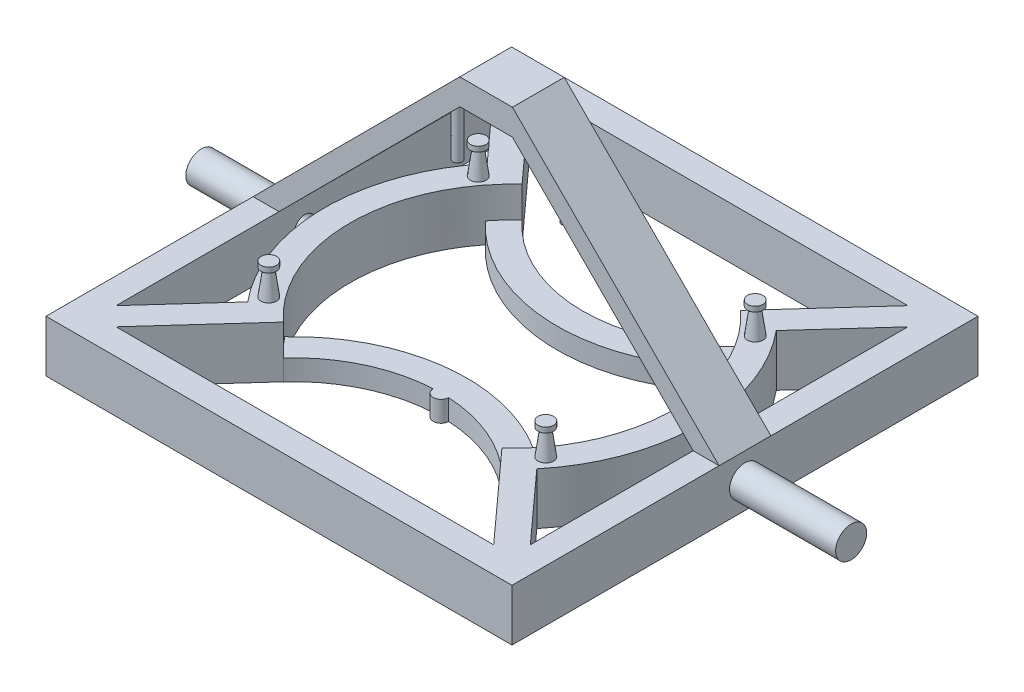
SolidWorks part; units mm, degrees
material "ABS PC"
ref_plane "Front Plane" through (0, 0, 0) normal (0, 0, 1) x (1, 0, 0)
ref_plane "Top Plane" through (0, 0, 0) normal (0, 1, 0) x (1, 0, 0)
ref_plane "Right Plane" through (0, 0, 0) normal (1, 0, 0) x (0, 0, -1)
sketch "Sketch1" plane through (0, 0, 0) normal (0, 1, 0) x (1, 0, 0)
  line L1 (-40, -40) -> (40, -40)
  line L2 (-40, -40) -> (-40, 40)
  line L3 (-40, 40) -> (40, 40)
  line L4 (40, -40) -> (40, 40)
  line L5 (-40, -40) -> (40, 40) construction
  line L6 (-40, 40) -> (40, -40) construction
  line L7 (-45, -45) -> (45, -45)
  line L8 (-45, -45) -> (-45, 45)
  line L9 (-45, 45) -> (45, 45)
  line L10 (45, -45) -> (45, 45)
  line L11 (-45, -45) -> (45, 45) construction
  line L12 (-45, 45) -> (45, -45) construction
  point P0 (0, 0)
  point P6 (0, 0)
  dimension "D1" = 80
  dimension "D2" = 5
extrude "Boss-Extrude1" add sketch "Sketch1" along normal blind 10
sketch "Sketch2" plane through (45, 0, 0) normal (1, 0, 0) x (0, 0, -1)
  line L0 (-45, 0) -> (45, 0) construction
  circle A0 centre (0, 5) radius 3
  dimension "D2" = 6
  dimension "D1" = 5
extrude "Boss-Extrude2" add sketch "Sketch2" along normal blind 20.5
sketch "Sketch3" plane through (0, 0, 0) normal (0, 0, 1) x (1, 0, 0)
  line L0 (-40, 10) -> (-45, 10)
  line L1 (-5.0739, 45) -> (-40, 10)
  line L2 (0, 0) -> (0, 50) construction
  line L3 (-5.0845, 50) -> (5.0845, 50)
  line L4 (5.0845, 50) -> (45, 10)
  line L5 (-5.0739, 45) -> (5.0739, 45)
  line L6 (5.0739, 45) -> (40, 10)
  line L7 (40, 10) -> (45, 10)
  line L8 (-5.0845, 50) -> (-45, 10)
  point P15 (0, 45)
  dimension "D1" = 50
  dimension "D2" = 5
extrude "Boss-Extrude3" add sketch "Sketch3" along normal blind 5 and the other way blind 5
sketch "Sketch4" plane through (-45, 0, 0) normal (-1, 0, 0) x (0, 0, 1)
  line L0 (5, 10) -> (45, 10) construction
  circle A0 centre (0, 5) radius 3
  dimension "D1" = 6
  dimension "D2" = 5
extrude "Boss-Extrude4" add sketch "Sketch4" along normal blind 15
sketch "Sketch5" plane through (0, 0, 0) normal (0, 1, 0) x (1, 0, 0)
  line L0 (-40, -5) -> (-40, -40) construction
  line L1 (-40, -40) -> (40, -40) construction
  line L4 (40, 40) -> (-40, 40) construction
  line L5 (-40, 40) -> (-40, 5) construction
  line L6 (-40, -36.4602) -> (-40, -40)
  line L7 (-40, -40) -> (-36.4602, -40)
  line L10 (-36.4602, 40) -> (-40, 40)
  line L11 (-40, 40) -> (-40, 36.4602)
  line L12 (-36.4602, 40) -> (-21.1018, 23.0494)
  line L13 (-27.9166, 23.1241) -> (-40, 36.4602)
  line L14 (-27.9166, -23.1241) -> (-40, -36.4602)
  line L15 (-36.4602, -40) -> (-21.1018, -23.0494)
  arc A0 (-21.1018, 23.0494) -> (-21.1018, -23.0494) centre (0, 0) ccw
  arc A1 (-27.9166, -23.1241) -> (-27.9166, 23.1241) centre (0, 0) cw
  dimension "D1" = 31.25
  dimension "D2" = 5
  dimension "D3" = 5
  dimension "D4" = 5
extrude "Boss-Extrude5" add sketch "Sketch5" along normal up to surface (10 mm away) up to face at (0, 10, -23.75)
mirror "Mirror1" about plane through (0, 0, 0) normal (1, 0, 0) of "Boss-Extrude5"
sketch "Sketch6" plane through (0, 0, 0) normal (0, 1, 0) x (1, 0, 0)
  line L8 (36.4602, 40) -> (21.1018, 23.0494) construction
  line L9 (-36.4602, 40) -> (-21.1018, 23.0494) construction
  line L10 (-60, 0) -> (65.5, 0) construction
  line L11 (-60, 3) -> (-60, -3) construction
  line L12 (65.5, -3) -> (65.5, 3) construction
  arc A0 (-21.1018, 23.0494) -> (-24.5175, 19.3767) centre (0, 0) ccw
  arc A2 (24.5175, 19.3767) -> (21.1018, 23.0494) centre (0, 0) ccw
  arc A7 (-21.1018, 23.0494) -> (21.1018, 23.0494) centre (0, 42.1691) ccw
  arc A9 (-21.1018, 23.0494) -> (-21.1018, -23.0494) centre (0, 0) ccw construction
  arc A10 (-24.5175, 19.3767) -> (24.5175, 19.3767) centre (0, 42.1691) ccw
  arc A11 (-24.5175, -19.3767) -> (24.5175, -19.3767) centre (0, -42.1691) cw
  arc A12 (-21.1018, -23.0494) -> (-24.5175, -19.3767) centre (0, 0) cw
  arc A13 (-21.1018, -23.0494) -> (-1.4995, -13.7332) centre (0, -42.1691) cw
  arc A14 (24.5175, -19.3767) -> (21.1018, -23.0494) centre (0, 0) cw
  arc A15 (-1.4995, -13.7332) -> (1.4995, -13.7332) centre (0, -13.6937) ccw
  arc A16 (1.4995, -13.7332) -> (21.1018, -23.0494) centre (0, -42.1691) cw
  dimension "D1" = 5
  dimension "D2" = 1.5
extrude "Boss-Extrude6" add sketch "Sketch6" along normal blind 4 contours A0 A10 A2 A7 | A11 A14 A16 A15 A13 A12
sketch "Sketch8" plane through (0, 10, 0) normal (0, 1, 0) x (1, 0, 0)
  circle A0 centre (-26.75, 20.2241) radius 1.5
  arc A2 (-21.1018, 23.0494) -> (-21.1018, -23.0494) centre (0, 0) ccw construction
  dimension "D2" = 3
  dimension "D1" = 26.75
  dimension "D3" = 2.9
extrude "Boss-Extrude7" add sketch "Sketch8" along normal blind 5 draft 8 contours A0
sketch "Sketch9" plane through (0, 15, 0) normal (0, 1, 0) x (1, 0, 0)
  circle A0 centre (-26.75, 20.2241) radius 1.5
  dimension "D1" = 3
extrude "Post for rubber bands" add sketch "Sketch9" along normal blind 1 contours A0
mirror "Mirror2" about plane through (0, 0, 0) normal (1, 0, 0) of "Boss-Extrude7", "Post for rubber bands"
mirror "Mirror3" about plane through (0, 0, 0) normal (0, 0, 1) of "Mirror2", "Boss-Extrude7", "Post for rubber bands"
ref_plane "Plane1" through (0, 41, 0) normal (0, -1, 0) x (-1, 0, 0)
sketch "Sketch12" plane through (0, 41, 0) normal (0, -1, 0) x (-1, 0, 0)
  circle A0 centre (-10.5, 0) radius 0.889
  circle A1 centre (10.5, 0) radius 0.889
  dimension "D4" = 1.778
  dimension "D1" = 21
  dimension "D3" = 10.5
extrude "Boss-Extrude10" add sketch "Sketch12" along normal blind 10
sketch "Sketch13" plane through (-60, 0, 0) normal (-1, 0, 0) x (0, 0, 1)
  circle A0 centre (0, 5) radius 2
  dimension "D1" = 4
extrude "Cut-Extrude1" cut sketch "Sketch13" against normal up to next
